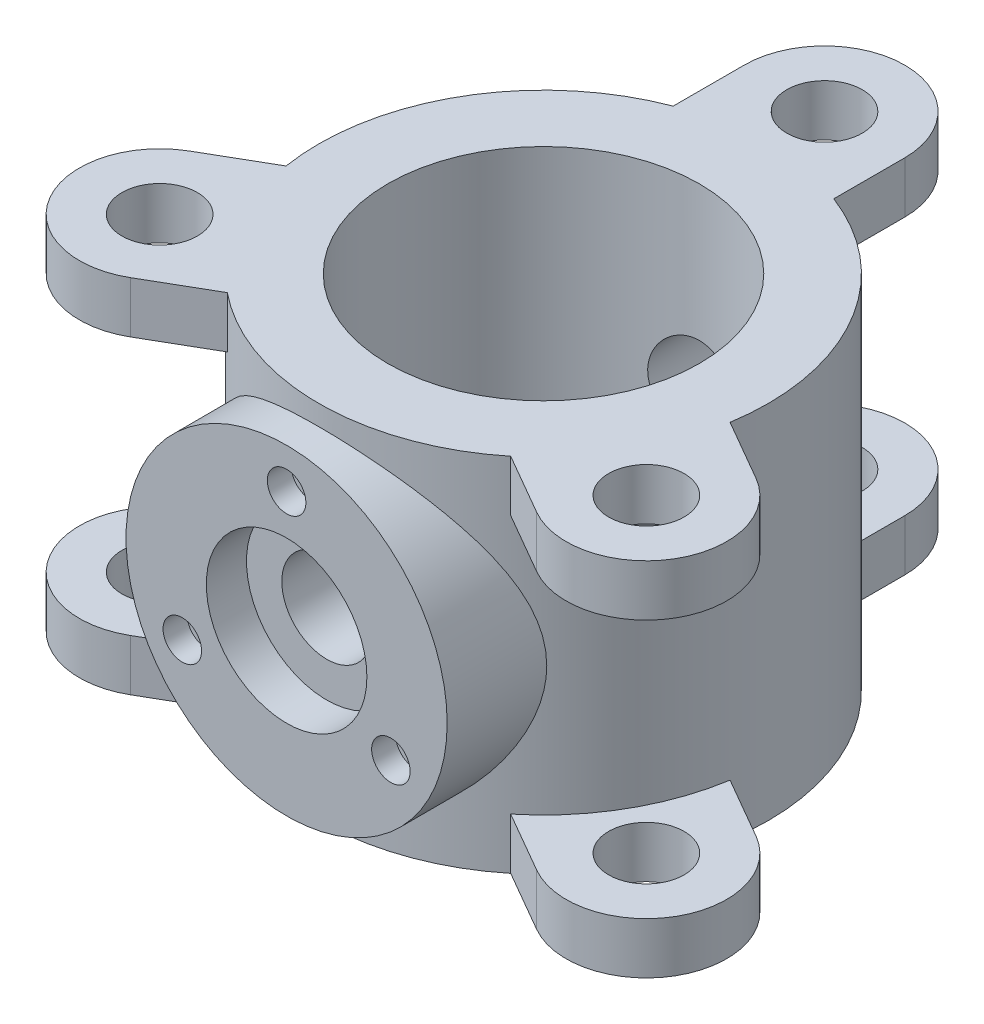
SolidWorks part; units mm, degrees
ref_plane "Front Plane" through (0, 0, 0) normal (0, 0, 1) x (1, 0, 0)
ref_plane "Top Plane" through (0, 0, 0) normal (0, 1, 0) x (1, 0, 0)
ref_plane "Right Plane" through (0, 0, 0) normal (1, 0, 0) x (0, 0, -1)
sketch "Sketch1" plane through (0, 0, 0) normal (0, 1, 0) x (1, 0, 0)
  circle A0 centre (0, 0) radius 140
  circle A1 centre (0, 0) radius 97
  dimension "D1" = 280
  dimension "D2" = 194
extrude "Boss-Extrude1" add sketch "Sketch1" along normal blind 225
sketch "Sketch2" plane through (0, 225, 0) normal (0, 1, 0) x (1, 0, 0)
  line L1 (-50, 114.6307) -> (50, 114.6307)
  line L2 (-50, 114.6307) -> (-50, 175)
  line L3 (-50, 175) -> (50, 175) construction
  line L4 (50, 114.6307) -> (50, 175)
  line L5 (-50, 114.6307) -> (50, 175) construction
  line L6 (-50, 175) -> (50, 114.6307) construction
  arc A0 (50, 175) -> (-50, 175) centre (0, 175) ccw
  circle A1 centre (0, 175) radius 23.5
  point P0 (0, 144.8154)
  dimension "D2" = 100
  dimension "D3" = 47
  dimension "D1" = 175
extrude "Boss-Extrude2" add sketch "Sketch2" against normal blind 32
pattern_circular "CirPattern1" count 3 over 360 about axis through (0, 0, 0) along (0, 1, 0) of "Boss-Extrude2"
ref_plane "Plane1" through (0, 112.5, 0) normal (0, 1, 0) x (1, 0, 0)
mirror "Mirror1" about plane through (0, 112.5, 0) normal (0, 1, 0) of "CirPattern1", "Boss-Extrude2"
ref_plane "Plane2" through (0, 0, 160) normal (0, 0, 1) x (1, 0, 0)
sketch "Sketch4" plane through (0, 0, 160) normal (0, 0, 1) x (1, 0, 0)
  circle A0 centre (0, 112.5) radius 100
  dimension "D1" = 200
  dimension "D2" = 112.5
extrude "Boss-Extrude3" add sketch "Sketch4" against normal up to next
sketch "Sketch5" plane through (0, 0, 160) normal (0, 0, 1) x (1, 0, 0)
  circle A0 centre (0, 112.5) radius 50
  dimension "D1" = 100
extrude "Cut-Extrude1" cut sketch "Sketch5" against normal blind 25
sketch "Sketch6" plane through (0, 0, 135) normal (0, 0, 1) x (1, 0, 0)
  circle A0 centre (0, 112.5) radius 28
  dimension "D1" = 56
extrude "Cut-Extrude2" cut sketch "Sketch6" against normal through all
sketch "Sketch7" plane through (0, 0, 160) normal (0, 0, 1) x (1, 0, 0)
  circle A0 centre (0, 187.5) radius 12
  circle A1 centre (0, 112.5) radius 50 construction
  point P4 (0, 0)
  dimension "D1" = 24
  dimension "D2" = 75
extrude "Cut-Extrude3" cut sketch "Sketch7" against normal blind 15
pattern_circular "CirPattern2" count 3 over 360 about axis through (0, 112.5, 0) along (0, 0, 1) of "Cut-Extrude3"
